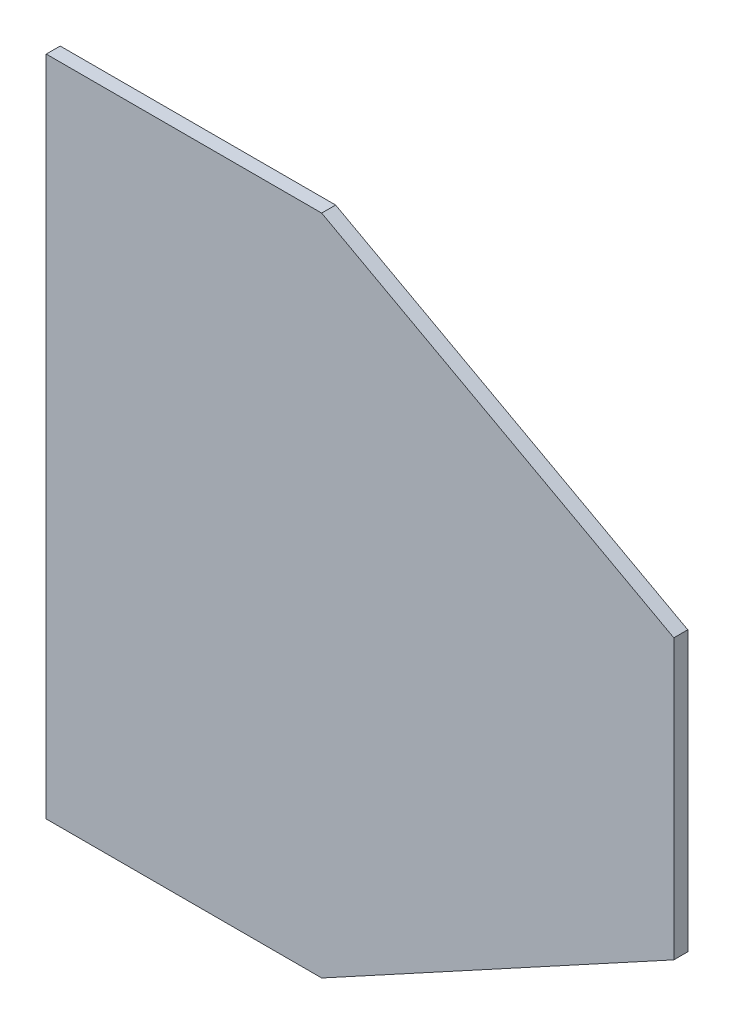
SolidWorks part; units mm, degrees
ref_plane "Front Plane" through (0, 0, 0) normal (0, 0, 1) x (1, 0, 0)
ref_plane "Top Plane" through (0, 0, 0) normal (0, 1, 0) x (1, 0, 0)
ref_plane "Right Plane" through (0, 0, 0) normal (1, 0, 0) x (0, 0, -1)
sketch "Sketch1" plane through (0, 0, 0) normal (0, 0, 1) x (1, 0, 0)
  line L0 (35, -64) -> (-44, -64)
  line L4 (-44, 126) -> (35, 126)
  line L5 (35, 126) -> (136, 71)
  line L6 (136, 71) -> (136, -9)
  line L7 (136, -9) -> (35, -64)
  line L8 (-44, -64) -> (-44, 126)
  dimension "D1" = 80
  dimension "D2" = 190
  dimension "D3" = 55
extrude "Boss-Extrude1" add sketch "Sketch1" along normal blind 4
